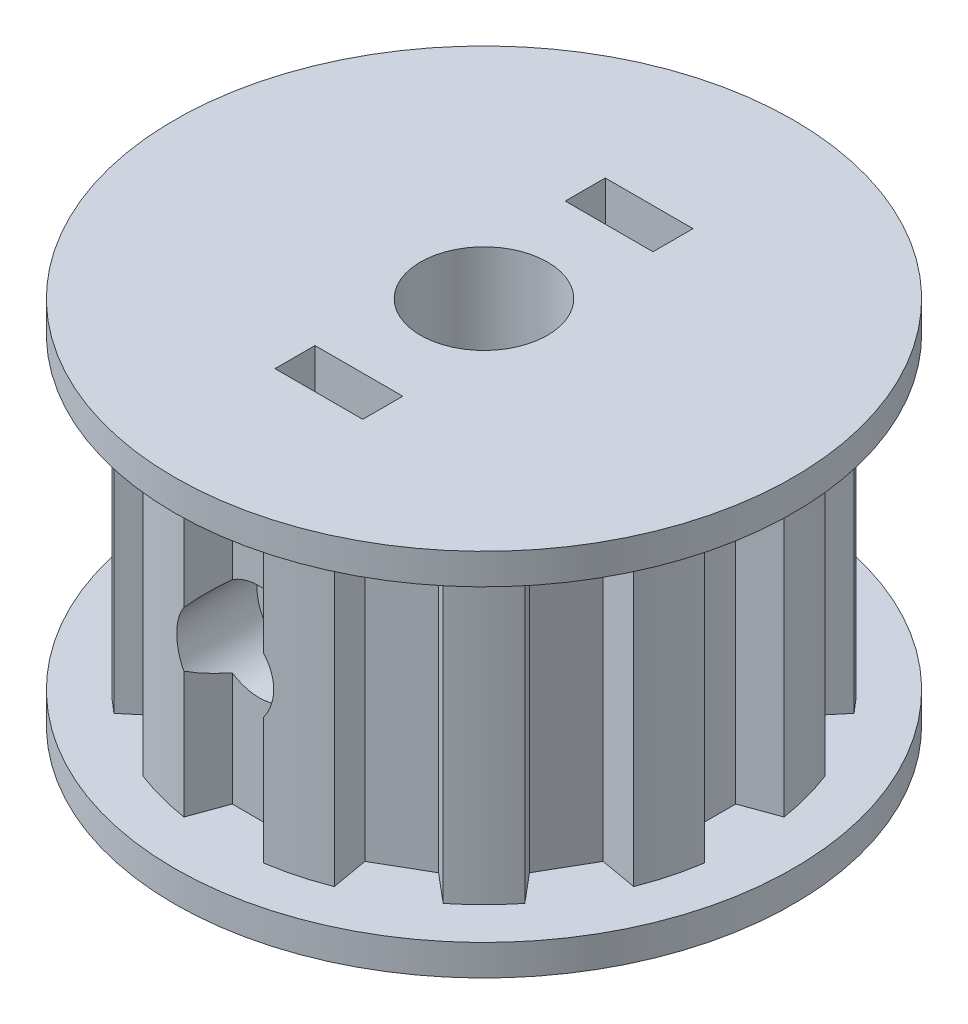
SolidWorks part; units mm, degrees
ref_plane "Front Plane" through (0, 0, 0) normal (0, 0, 1) x (1, 0, 0)
ref_plane "Top Plane" through (0, 0, 0) normal (0, 1, 0) x (1, 0, 0)
ref_plane "Right Plane" through (0, 0, 0) normal (1, 0, 0) x (0, 0, -1)
sketch "Sketch2" plane through (0, 0, 0) normal (0, 1, 0) x (1, 0, 0)
  circle A0 centre (0, 0) radius 19.0986
  dimension "D1" = 38.1972
extrude "Boss-Extrude2" add sketch "Sketch2" along normal blind 20
sketch "Sketch3" plane through (0, 20, 0) normal (0, 1, 0) x (1, 0, 0)
  line L0 (0, 9.5495) -> (0, -19.0986) construction
  line L1 (19.0986, 0) -> (-19.0986, 0) construction
  line L2 (1.75, 14.5986) -> (-1.75, 14.5986)
  line L3 (-1.75, 14.5986) -> (-2.5882, 16.9016)
  line L4 (0, 0) -> (-4.9431, 18.4478) construction
  line L5 (-4.9431, 18.4478) -> (-4.4254, 16.516)
  line L6 (1.75, 14.5986) -> (2.5882, 16.9016)
  line L7 (4.9431, 18.4478) -> (4.4254, 16.516)
  circle A0 centre (0, 0) radius 14.5986 construction
  circle A1 centre (0, 0) radius 17.0986 construction
  circle A2 centre (0, 0) radius 19.0986 construction
  arc A3 (-2.5882, 16.9016) -> (-4.4254, 16.516) centre (0, 0) ccw
  arc A4 (4.9431, 18.4478) -> (-4.9431, 18.4478) centre (0, 0) ccw
  arc A5 (2.5882, 16.9016) -> (4.4254, 16.516) centre (0, 0) cw
  circle A6 centre (0, 0) radius 4.125 construction
  point P21 (0, 14.5986)
  dimension "D1" = 29.1972
  dimension "D2" = 34.1972
  dimension "D6" = 8.25
  dimension "D3" = 20
  dimension "D4" = 3.5
  dimension "D5" = 15
extrude "Cut-Extrude1" cut sketch "Sketch3" against normal blind 20
pattern_circular "CirPattern2" count 12 over 360 about axis through (0, 0, 0) along (0, 1, 0) of "Cut-Extrude1"
sketch "Sketch6" plane through (0, 20, 0) normal (0, 1, 0) x (1, 0, 0)
  circle A0 centre (0, 0) radius 20.0986
  dimension "D1" = 40.1972
extrude "Boss-Extrude3" add sketch "Sketch6" along normal blind 2
sketch "Sketch7" plane through (0, 0, 0) normal (0, -1, 0) x (1, 0, 0)
  circle A0 centre (0, 0) radius 20.0986
  circle A1 centre (0, 0) radius 20.0986 construction
extrude "Boss-Extrude4" add sketch "Sketch7" along normal blind 2
sketch "Sketch8" plane through (0, -2, 0) normal (0, -1, 0) x (1, 0, 0)
  line L0 (0, 0) -> (0, 20.0986) construction
  line L1 (-20.0986, 0) -> (20.0986, 0) construction
  line L2 (-2.85, 8.125) -> (2.85, 8.125)
  line L3 (-2.85, 8.125) -> (-2.85, 10.725)
  line L4 (-2.85, 10.725) -> (2.85, 10.725)
  line L5 (2.85, 8.125) -> (2.85, 10.725)
  line L6 (-2.85, 8.125) -> (2.85, 10.725) construction
  line L7 (-2.85, 10.725) -> (2.85, 8.125) construction
  line L8 (-2.85, -10.725) -> (2.85, -10.725)
  line L9 (2.85, -8.125) -> (2.85, -10.725)
  line L10 (-2.85, -8.125) -> (2.85, -8.125)
  line L11 (-2.85, -8.125) -> (-2.85, -10.725)
  circle A0 centre (0, 0) radius 4.125
  circle A1 centre (0, 0) radius 20.0986 construction
  point P6 (0, 9.425)
  dimension "D1" = 8.25
  dimension "D2" = 5.7
  dimension "D3" = 2.6
  dimension "D4" = 8.125
extrude "Cut-Extrude3" cut sketch "Sketch8" against normal through all both and the other way through all
sketch "Sketch10" plane through (0, 0, -14.5986) normal (0, 0, -1) x (-1, 0, 0)
  line L0 (0, 0) -> (0, 20) construction
  line L1 (1.75, 0) -> (-1.75, 0) construction
  line L2 (1.75, 20) -> (-1.75, 20) construction
  circle A0 centre (0, 10) radius 1.5
  dimension "D1" = 3
extrude "Cut-Extrude4" cut sketch "Sketch10" against normal through all both
sketch "Sketch11" plane through (0, 0, -14.5986) normal (0, 0, -1) x (-1, 0, 0)
  circle A0 centre (0, 10) radius 3.175
  dimension "D1" = 6.35
extrude "Cut-Extrude5" cut sketch "Sketch11" against normal blind 3 and the other way blind 10
sketch "Sketch12" plane through (0, 0, 14.5986) normal (0, 0, 1) x (1, 0, 0)
  circle A0 centre (0, 10) radius 3.15
  dimension "D1" = 6.3
extrude "Cut-Extrude6" cut sketch "Sketch12" against normal blind 3 and the other way blind 10
equation "\"n\" = 12'number of teeth"
equation "\"hs\"= 4.5mm'belt height"
equation "\"ht\"= 2.5mm'tooth height"
equation "\"t\"= 10mm'tooth pitch"
equation "\"beta\"= 40deg'tooth angle"
equation "\"s\"= 3.5mm'tooth width"
equation "\"do\"= \"n\" * \"t\" / pi'outer diameter"
equation "\"di\"= \"do\" - 2 * ( \"hs\" - \"ht\" )'inner diameter"
equation "\"dm\"= \"do\" - 2 * \"hs\"'midle diameter"
equation "\"theta\"= 360deg / ( 2 * \"n\" )'angle"
equation "\"D1@Sketch2\"=\"do\""
equation "\"D5@Sketch3\"=\"theta\""
equation "\"D3@Sketch3\"=\"beta\"/2"
equation "\"D4@Sketch3\"=\"s\""
equation "\"D2@Sketch3\"=\"di\""
equation "\"D1@Sketch3\"=\"dm\""
equation "\"D1@CirPattern2\"=\"n\""
equation "\"db\"= 8.25mm'center bore diameter"
equation "\"bw\"= 16mm'width of belt"
equation "\"hi\"= \"bw\" + 4mm'height of teeth"
equation "\"w\"= 2mm'width of protective layer"
equation "\"de\"= \"do\" + 2mm'diameter of protective layer"
equation "\"D1@Boss-Extrude2\"=\"hi\""
equation "\"D1@Cut-Extrude1\"=\"hi\""
equation "\"D1@Sketch6\"=\"de\""
equation "\"D1@Boss-Extrude3\"=\"w\""
equation "\"D1@Boss-Extrude4\"=\"w\""
equation "\"D1@Sketch8\"=\"db\""
equation "\"D6@Sketch3\"=\"db\""
